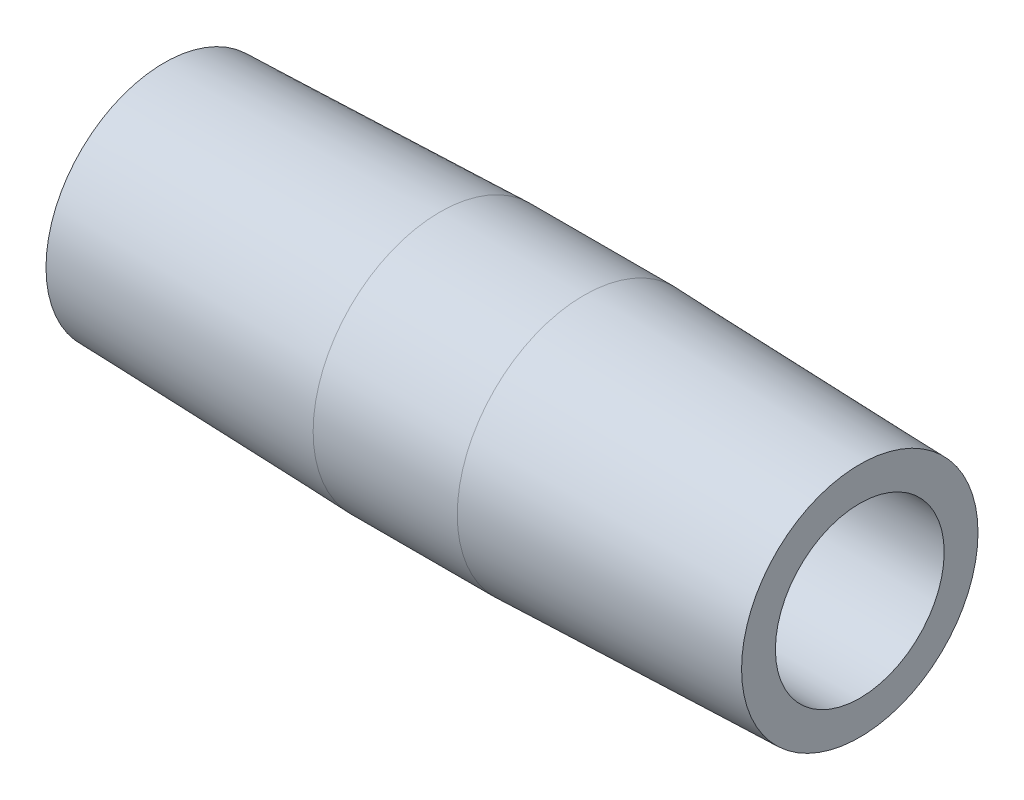
SolidWorks part; units mm, degrees
material "Chrome Stainless Steel"
ref_plane "Front Plane" through (0, 0, 0) normal (0, 0, 1) x (1, 0, 0)
ref_plane "Top Plane" through (0, 0, 0) normal (0, 1, 0) x (1, 0, 0)
ref_plane "Right Plane" through (0, 0, 0) normal (1, 0, 0) x (0, 0, -1)
sketch "Sketch1" plane through (0, 0, 0) normal (0, 0, 1) x (1, 0, 0)
  line L0 (-19.05, 0) -> (19.05, 0) construction
  line L1 (19.05, 6.9453) -> (19.05, -6.9453) construction
  line L2 (-19.05, 6.9453) -> (-19.05, -6.9453) construction
  point P6 (3.9472, 0)
  point P8 (-3.9472, 0)
  point P9 (-3.9472, 6.9453)
  point P10 (-3.9472, -6.9453)
  point P11 (3.9472, 6.9453)
  point P12 (3.9472, -6.9453)
  point P13 (10.2972, 6.9453)
  point P14 (10.2972, -6.9453)
  dimension "D1" = 13.8906
  dimension "D" = 38.1
  dimension "D2" = 15.1028
  dimension "D3" = 6.35
ref_plane "Plane1" through (3.9472, 0, 0) normal (1, 0, 0) x (0, 0, -1)
sketch "Sketch2" plane through (3.9472, 0, 0) normal (1, 0, 0) x (0, 0, -1)
  circle A0 centre (0, 0) radius 6.9453
extrude "Extrude1" add sketch "Sketch2" along normal up to vertex (15.1028 mm away) draft 1.783 up to point (19.05, 0, 0)
sketch "Sketch5" plane through (19.05, 0, 0) normal (1, 0, 0) x (0, 0, -1)
  circle A3 centre (0, 0) radius 4.6228
  dimension "ID" = 9.2456
sketch "Sketch10" plane through (3.9472, 0, 0) normal (-1, 0, 0) x (0, 0, 1)
  circle A0 centre (0, 0) radius 6.598
  dimension "D1" = 13.1961
sketch "Sketch13" plane through (3.9472, 0, 0) normal (-1, 0, 0) x (0, 0, 1)
  circle A1 centre (0, 0) radius 6.598
  circle A2 centre (0, 0) radius 6.598
  dimension "D1" = 0
sketch "Sketch11" plane through (3.9472, 0, 0) normal (-1, 0, 0) x (0, 0, 1)
  circle A0 centre (0, 0) radius 6.9453
  dimension "D1" = 13.8906
extrude "Extrude4" add sketch "Sketch11" along normal up to vertex (3.9472 mm away) separate body up to point (0, 0, 0)
extrude "Extrude5" add sketch "Sketch13" along normal blind 1.0583
mirror "Mirror1" [suppressed] about plane through (0, 0, 0) normal (1, 0, 0)
ref_axis "Axis1" through (0, 27.1822, 0) along (0, -1, 0)
pattern_circular "CirPattern1" count 2 over 360 about axis through (0, 27.1822, 0) along (0, -1, 0) of bodies 112
combine bodies "Combine1" operation type add bodies to combine 112 113
extrude "Cut-Extrude3" cut sketch "Sketch5" against normal through all
equation "\"D1@Sketch1\" = \"pipe od@Sketch1\""
equation "\"D2@Sketch1\" = \"R@Sketch1\""
equation "\"D1@Sketch10\" = \"pipe od@Sketch1\"*.95"
equation "\"D1@Sketch11\" = \"pipe od@Sketch1\""
